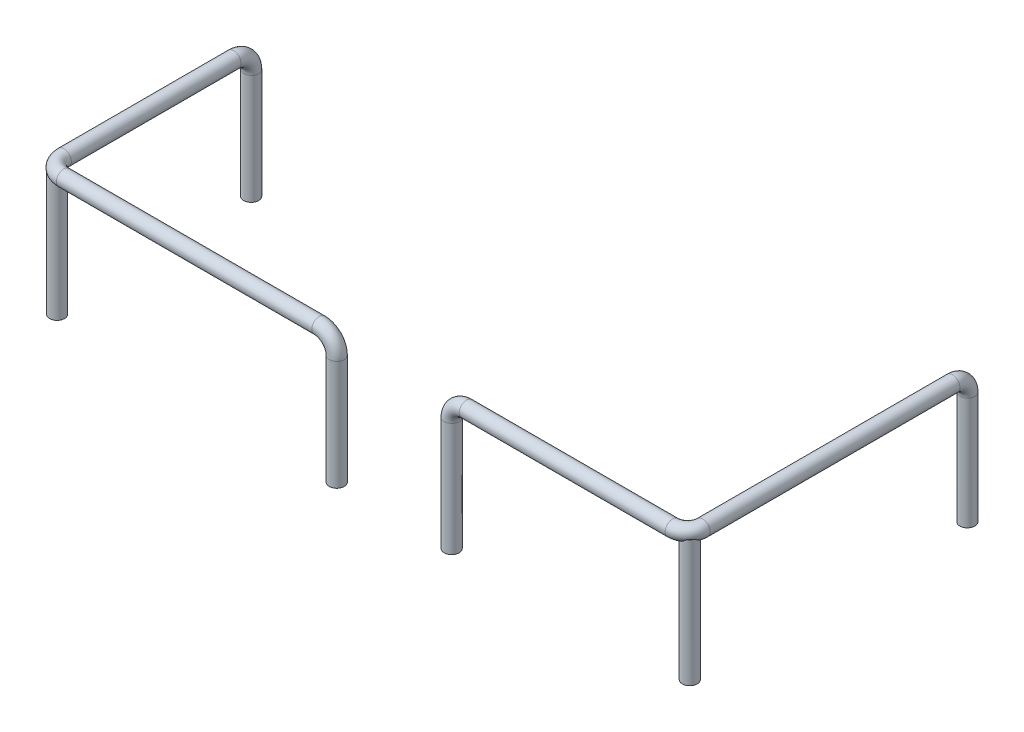
SolidWorks part; units mm, degrees
ref_plane "Alzado" through (0, 0, 0) normal (0, 0, 1) x (1, 0, 0)
ref_plane "Planta" through (0, 0, 0) normal (0, 1, 0) x (1, 0, 0)
ref_plane "Vista lateral" through (0, 0, 0) normal (1, 0, 0) x (0, 0, -1)
sketch "Croquis1" plane through (0, 0, 0) normal (0, 1, 0) x (1, 0, 0)
  line L0 (0, 0) -> (0, 1700) construction
  line L1 (0, 0) -> (2460, 0) construction
  line L2 (2460, 0) -> (2400, 0) construction
  line L3 (0, 1700) -> (0, 1640) construction
  line L4 (0, 0) -> (659.4927, 678.0888) construction
  circle A0 centre (2400, 0) radius 60
  circle A1 centre (0, 1640) radius 60
  circle A2 centre (0, 0) radius 60
  dimension "D5" = 120
  dimension "D1" = 2460
  dimension "D2" = 1700
  dimension "D3" = 60
  dimension "D4" = 60
sketch3d "Croquis3D3"
  line L0 (0, 0, -1640) -> (0, 880, -1640)
  line L1 (2325, 0, 0) -> (2325, 880, 0)
  line L2 (0, 0, 0) -> (2460, 0, 0) construction
  line L3 (0, 0, 0) -> (0, 1020, 0) construction
  line L4 (0, 1020, -1500) -> (0, 1020, -140)
  line L5 (140, 1020, 0) -> (2185, 1020, 0)
  arc A0 (0, 1020, -140) -> (140, 1020, 0) centre (140, 1020, -140) ccw
  arc A1 (2185, 1020, 0) -> (2325, 880, 0) centre (2185, 880, 0) ccw
  arc A2 (0, 880, -1640) -> (0, 1020, -1500) centre (0, 880, -1500) ccw
  point P12 (0, 1020, 0)
  point P14 (140, 1160, -140)
  point P17 (2325, 1020, 0)
  point P18 (2185, 880, -140)
  point P21 (0, 1020, -1640)
  point P22 (140, 880, -1500)
  dimension "D1" = 140
  dimension "D3" = 140
  dimension "D2" = 1020
extrude "Saliente-Extruir1" add sketch "Croquis1" along normal blind 10 contours A1
sketch "Croquis2" plane through (0, 10, 0) normal (0, 1, 0) x (1, 0, 0)
  circle A0 centre (0, 1640) radius 60
  circle A1 centre (0, 1640) radius 60 construction
sweep "Barrer4" add profiles "Croquis2" path "Croquis3D3"
sketch "Croquis4" plane through (0, 0, 0) normal (0, 1, 0) x (1, 0, 0)
  circle A0 centre (41.1944, 44.3898) radius 60
  dimension "D1" = 120
extrude "Saliente-Extruir3" add sketch "Croquis4" along normal blind 1020
ref_plane "Plano1" through (0, 0, 0) normal (0, 0, 1) x (1, 0, 0)
sketch "Croquis5" plane through (0, 0, 0) normal (0, 1, 0) x (1, 0, 0)
  line L0 (2385, 0) -> (3185, 0) construction
  circle A0 centre (2325, 0) radius 60 construction
  circle A1 centre (3245, 0) radius 60
  dimension "D2" = 120
  dimension "D1" = 800
extrude "Saliente-Extruir4" add sketch "Croquis5" along normal blind 10 separate body
sketch3d "Croquis3D4"
  line L0 (3245, 10, 0) -> (3245, 910, 0)
  line L1 (3245, 10, 0) -> (3245, 0, 0) construction
  line L2 (5014.1287, 1030, 0) -> (3365, 1030, 0)
  line L3 (5134.1287, 910, 0) -> (5134.1287, 10, 0) construction
  line L4 (5134.1287, 1030, -120) -> (5134.1287, 1030, -2120)
  line L5 (5134.1287, 910, -2240) -> (5134.1287, 10, -2240)
  arc A0 (5134.1287, 1030, -2120) -> (5134.1287, 910, -2240) centre (5134.1287, 910, -2120) ccw
  arc A1 (5134.1287, 1030, -120) -> (5014.1287, 1030, 0) centre (5014.1287, 1030, -120) ccw
  arc A2 (5014.1287, 1030, 0) -> (5134.1287, 910, 0) centre (5014.1287, 910, 0) ccw construction
  arc A3 (3245, 910, 0) -> (3365, 1030, 0) centre (3365, 910, 0) ccw
  point P11 (5134.1287, 1030, -2240)
  point P14 (5134.1287, 1030, 0)
  point P15 (5014.1287, 910, -120)
  point P18 (3245, 1030, 0)
  point P19 (3365, 910, -120)
  point P20 (5014.1287, 910, -2120)
  point P23 (5134.1287, 1030, 0)
  point P24 (5014.1287, 910, -120)
  dimension "D3" = 120
  dimension "D6" = 120
  dimension "D7" = 120
  dimension "D1" = 1020
  dimension "D2" = 1020
  dimension "D4" = 1020
  dimension "D5" = 2240
sketch "Croquis6" plane through (0, 10, 0) normal (0, 1, 0) x (1, 0, 0)
  circle A0 centre (3245, 0) radius 60
sweep "Barrer6" add profiles "Croquis6" path "Croquis3D4"
sketch "Croquis7" plane through (0, 0, 0) normal (0, 1, 0) x (1, 0, 0)
  line L0 (41.1944, 44.3898) -> (5107.1027, 44.3898) construction
  circle A0 centre (5107.1027, 44.3898) radius 60
  dimension "D1" = 120
  dimension "D2" = 5065.9083
extrude "Saliente-Extruir5" add sketch "Croquis7" along normal blind 1011
ref_plane "Plano2" through (0, 0, 0) normal (0, 0, 1) x (1, 0, 0)
ref_plane "Plano3" through (0, 0, 0) normal (1, 0, 0) x (0, 0, -1)
